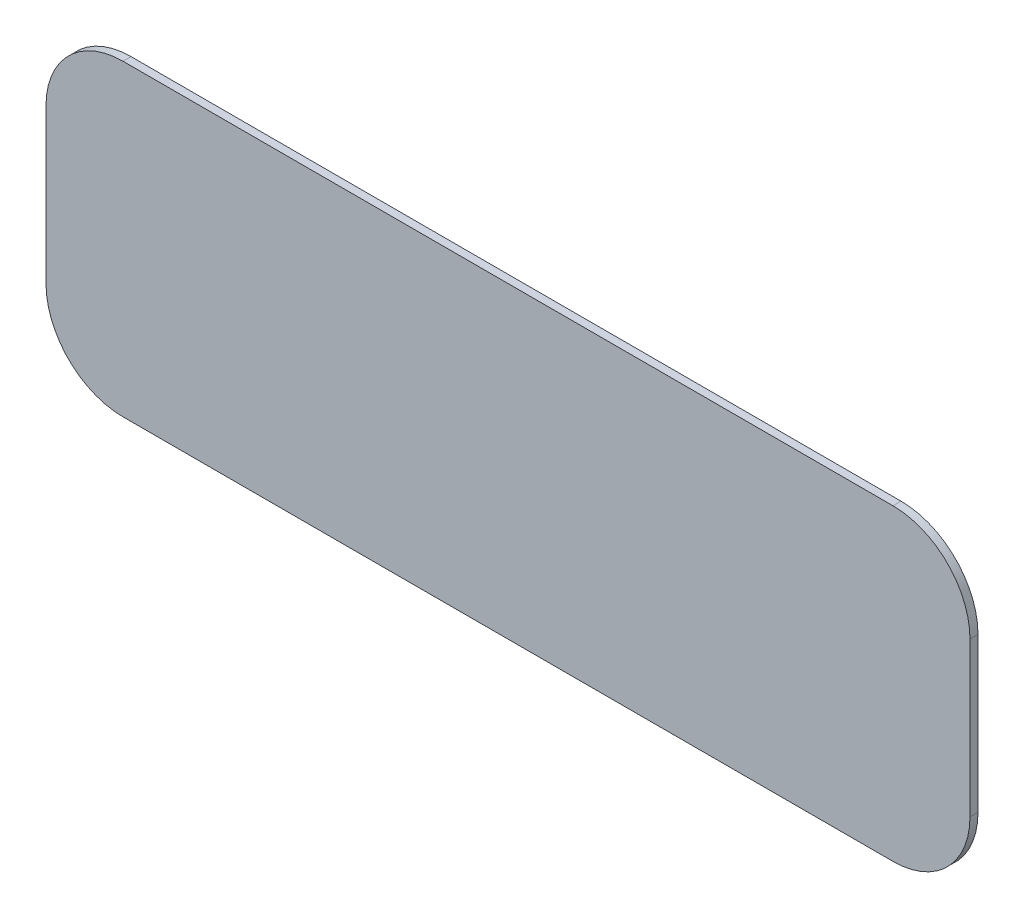
SolidWorks part; units mm, degrees
ref_plane "Front Plane" through (0, 0, 0) normal (0, 0, 1) x (1, 0, 0)
ref_plane "Top Plane" through (0, 0, 0) normal (0, 1, 0) x (1, 0, 0)
ref_plane "Right Plane" through (0, 0, 0) normal (1, 0, 0) x (0, 0, -1)
sketch "Sketch1" plane through (0, 0, 0) normal (0, 0, 1) x (1, 0, 0)
  line L1 (-76.2, -30.48) -> (76.2, -30.48)
  line L2 (-91.44, -15.24) -> (-91.44, 15.24)
  line L3 (-76.2, 30.48) -> (76.2, 30.48)
  line L4 (91.44, -15.24) -> (91.44, 15.24)
  line L5 (-91.44, -30.48) -> (91.44, 30.48) construction
  line L6 (-91.44, 30.48) -> (91.44, -30.48) construction
  arc A0 (91.44, -15.24) -> (76.2, -30.48) centre (76.2, -15.24) cw
  arc A1 (91.44, 15.24) -> (76.2, 30.48) centre (76.2, 15.24) ccw
  arc A2 (-91.44, -15.24) -> (-76.2, -30.48) centre (-76.2, -15.24) ccw
  arc A3 (-91.44, 15.24) -> (-76.2, 30.48) centre (-76.2, 15.24) cw
  point P0 (0, 0)
  dimension "D3" = 15.24
  dimension "D1" = 182.88
  dimension "D2" = 60.96
extrude "Boss-Extrude1" add sketch "Sketch1" along normal blind 1.5875 contours L3 A1 L4 A0 L1 A2 L2 A3
